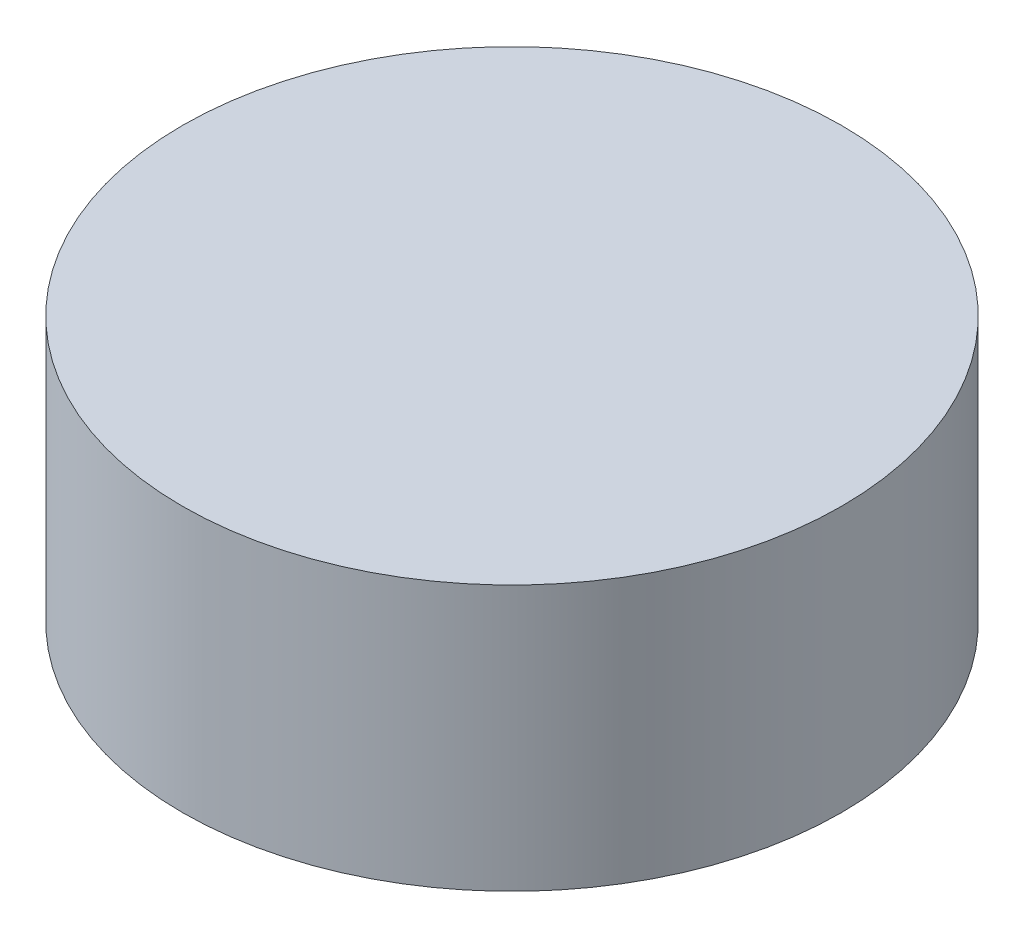
SolidWorks part; units mm, degrees
material "ABS"
ref_plane "Front Plane" through (0, 0, 0) normal (0, 0, 1) x (1, 0, 0)
ref_plane "Top Plane" through (0, 0, 0) normal (0, 1, 0) x (1, 0, 0)
ref_plane "Right Plane" through (0, 0, 0) normal (1, 0, 0) x (0, 0, -1)
sketch "Sketch1" plane through (0, 0, 0) normal (0, 1, 0) x (1, 0, 0)
  circle A0 centre (0, 0) radius 42
  circle A1 centre (0, 0) radius 43.5
  dimension "D1" = 84
  dimension "D2" = 87
extrude "Boss-Extrude1" add sketch "Sketch1" along normal blind 32
sketch "Sketch2" plane through (0, 32, 0) normal (0, 1, 0) x (1, 0, 0)
  circle A0 centre (0, 0) radius 43.5
extrude "Boss-Extrude2" add sketch "Sketch2" along normal blind 3
